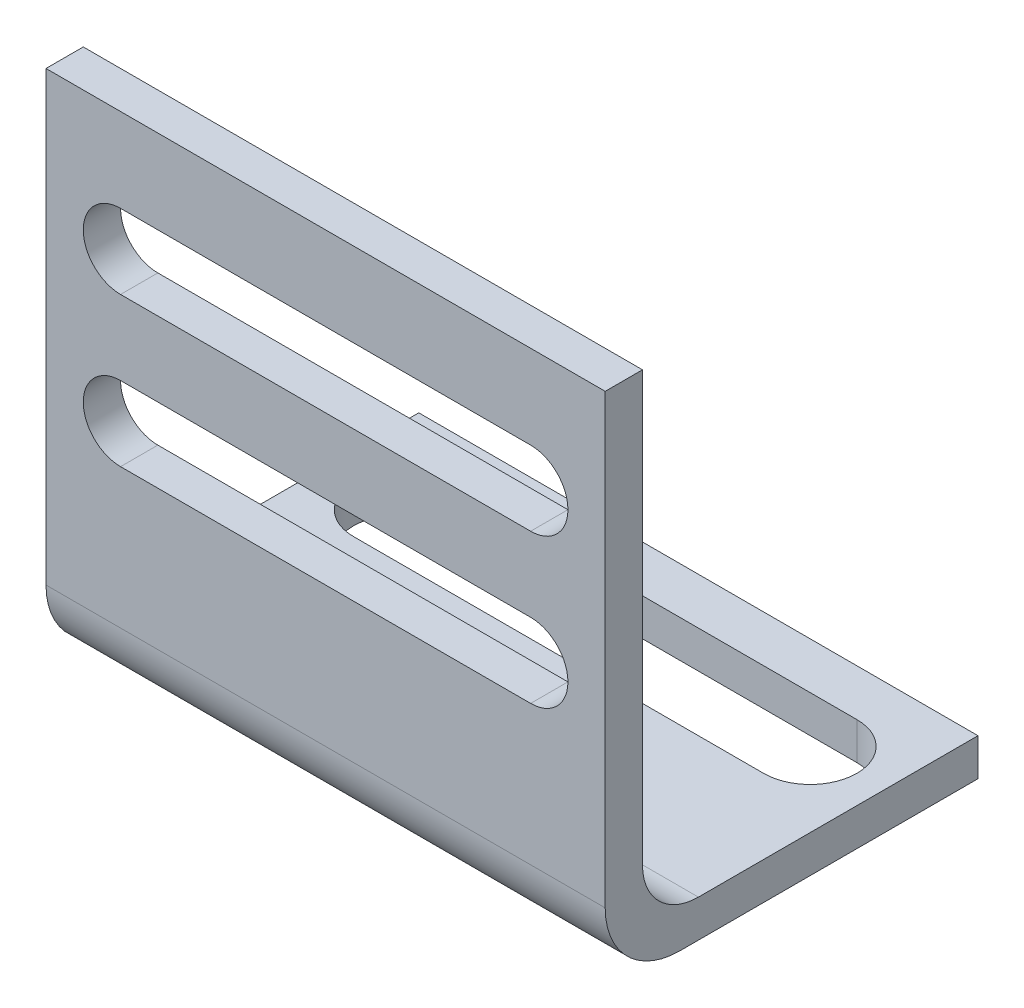
SolidWorks part; units mm, degrees
material "AISI 304"
ref_plane "前视基准面" through (0, 0, 0) normal (0, 0, 1) x (1, 0, 0)
ref_plane "上视基准面" through (0, 0, 0) normal (0, 1, 0) x (1, 0, 0)
ref_plane "右视基准面" through (0, 0, 0) normal (1, 0, 0) x (0, 0, -1)
sketch "草图1" plane through (0, 0, 0) normal (1, 0, 0) x (0, 0, -1)
  line L0 (0, 0) -> (0, -17.4575)
  line L1 (3.576, -28) -> (20, -28)
  line L6 (2, 0) -> (2, -18.3505)
  line L7 (3.7462, -26) -> (20, -26)
  line L8 (0, 0) -> (2, 0)
  line L9 (20, -26) -> (20, -28)
  line L10 (0, -17.4575) -> (0, -28)
  line L11 (0, -28) -> (3.576, -28)
  line L12 (2, -18.3505) -> (2, -26)
  line L13 (2, -26) -> (3.7462, -26)
  arc A3 (0, -17.4575) -> (3.576, -28) centre (4.545, -21.7936) ccw construction
  arc A4 (2, -18.3505) -> (3.7462, -26) centre (4.545, -21.7936) ccw construction
  point P6 (0, -28)
  dimension "D1" = 28
  dimension "D2" = 20
  dimension "D4" = 2
extrude "凸台-拉伸1" add sketch "草图1" along normal blind 30
sketch "草图3" plane through (0, 0, 0) normal (0, 0, 1) x (1, 0, 0)
  line L0 (0, -28) -> (0, -14.5) construction
  line L1 (0, -14.5) -> (31.9752, -14.5) construction
  line L2 (0, -14.5) -> (0, -6.5) construction
  line L3 (0, 0) -> (0, -28) construction
  line L4 (0, -6.5) -> (35.1319, -6.5) construction
  line L5 (4, -14.5) -> (26, -14.5) construction
  line L6 (4, -12.5) -> (26, -12.5)
  line L7 (4, -16.5) -> (26, -16.5)
  line L8 (4, -6.5) -> (26, -6.5) construction
  line L9 (4, -4.5) -> (26, -4.5)
  line L10 (4, -8.5) -> (26, -8.5)
  line L11 (30, 0) -> (30, -28) construction
  arc A0 (4, -12.5) -> (4, -16.5) centre (4, -14.5) ccw
  arc A1 (26, -16.5) -> (26, -12.5) centre (26, -14.5) ccw
  arc A2 (4, -4.5) -> (4, -8.5) centre (4, -6.5) ccw
  arc A3 (26, -8.5) -> (26, -4.5) centre (26, -6.5) ccw
  point P11 (15, -14.5)
  point P16 (15, -6.5)
  dimension "D3" = 2
  dimension "D4" = 2
  dimension "D1" = 13.5
  dimension "D2" = 8
  dimension "D5" = 4
  dimension "D6" = 4
  dimension "D7" = 4
  dimension "D8" = 4
extrude "切除-拉伸1" cut sketch "草图3" against normal through all
sketch "草图4" plane through (0, -28, 0) normal (0, -1, 0) x (1, 0, 0)
  line L0 (0, 0) -> (0, -15) construction
  line L1 (0, 0) -> (0, -20) construction
  line L2 (0, -15) -> (33.3758, -15) construction
  line L3 (4, -15) -> (26, -15) construction
  line L4 (4, -12.5) -> (26, -12.5)
  line L5 (4, -17.5) -> (26, -17.5)
  line L6 (30, 0) -> (30, -20) construction
  arc A0 (4, -12.5) -> (4, -17.5) centre (4, -15) ccw
  arc A1 (26, -17.5) -> (26, -12.5) centre (26, -15) ccw
  point P8 (15, -15)
  dimension "D2" = 2.5
  dimension "D1" = 15
  dimension "D3" = 4
  dimension "D4" = 4
extrude "切除-拉伸2" cut sketch "草图4" against normal through all
fillet "圆角2" radius 4 1 edges at (15, -28, 0)
fillet "圆角3" radius 3 1 edges at (15, -26, -2)
